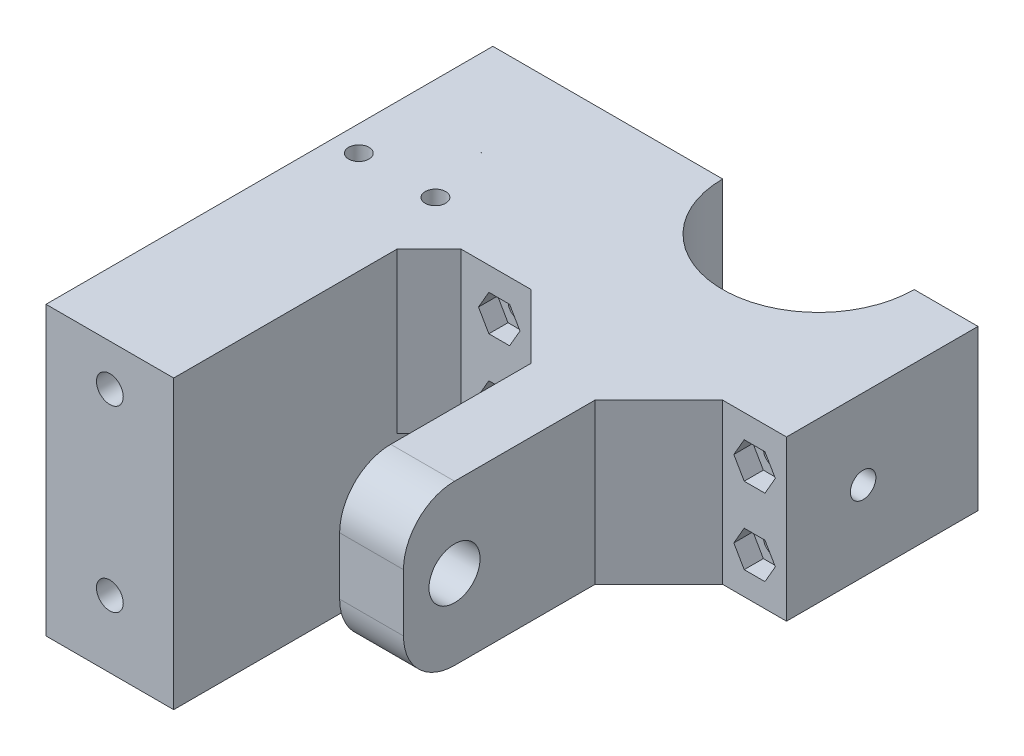
SolidWorks part; units mm, degrees
ref_plane "Спереди" through (0, 0, 0) normal (0, 0, 1) x (1, 0, 0)
ref_plane "Сверху" through (0, 0, 0) normal (0, 1, 0) x (1, 0, 0)
ref_plane "Справа" through (0, 0, 0) normal (1, 0, 0) x (0, 0, -1)
sketch "Sketch1" plane through (0, 0, 0) normal (0, 1, 0) x (1, 0, 0)
  line L0 (26.0276, -8) -> (-23.9724, -8) construction
  line L1 (-13.9724, -8) -> (-23.9724, -8)
  line L2 (-23.9724, -8) -> (-23.9724, -38)
  line L3 (-23.9724, -38) -> (-3.9724, -38)
  line L4 (-3.9724, -38) -> (-3.9724, -78)
  line L5 (-3.9724, -78) -> (6.0276, -78)
  line L6 (6.0276, -78) -> (6.0276, -38)
  line L7 (6.0276, -38) -> (26.0276, -38)
  line L8 (26.0276, -38) -> (26.0276, -8)
  line L9 (16.0276, -8) -> (26.0276, -8)
  circle A0 centre (1.0276, -8) radius 15 construction
  arc A1 (-13.9724, -8) -> (16.0276, -8) centre (1.0276, -8) ccw
  dimension "D2" = 30
  dimension "D1" = 30
  dimension "D3" = 10
  dimension "D4" = 40
  dimension "D5" = 50
extrude "Boss-Extrude1" add sketch "Sketch1" along normal blind 25
sketch "Sketch2" plane through (-3.9724, 0, 0) normal (-1, 0, 0) x (0, 0, 1)
  line L0 (78, 12.5) -> (38, 12.5) construction
  line L1 (78, 25) -> (78, 0) construction
  line L2 (38, 25) -> (38, 0) construction
  circle A0 centre (70, 12.5) radius 4
  dimension "D1" = 8
  dimension "D2" = 8
extrude "Cut-Extrude1" cut sketch "Sketch2" against normal through all
sketch "Sketch3" plane through (0, 0, 8) normal (0, 0, -1) x (-1, 0, 0)
  line L0 (-21.0276, 0) -> (-21.0276, 25) construction
  line L1 (-26.0276, 0) -> (-16.0276, 0) construction
  line L2 (-26.0276, 25) -> (-16.0276, 25) construction
  line L3 (18.9724, 0) -> (18.9724, 25) construction
  line L4 (13.9724, 0) -> (23.9724, 0) construction
  line L5 (13.9724, 25) -> (23.9724, 25) construction
  line L6 (-21.0276, 6.5) -> (18.9724, 6.5) construction
  line L7 (-21.0276, 18.5) -> (18.9724, 18.5) construction
  circle A0 centre (-21.0276, 6.5) radius 1.6
  circle A1 centre (-21.0276, 18.5) radius 1.6
  circle A2 centre (18.9724, 6.5) radius 1.6
  circle A3 centre (18.9724, 18.5) radius 1.6
  point P16 (-21.0276, 12.5)
  dimension "D2" = 3.2
  dimension "D3" = 12
  dimension "D4" = 6
extrude "Cut-Extrude2" cut sketch "Sketch3" against normal through all
sketch "Sketch4" plane through (0, 0, 38) normal (0, 0, 1) x (1, 0, 0)
  line L1 (24.2776, 18.5) -> (22.6526, 21.3146)
  line L2 (22.6526, 21.3146) -> (19.4026, 21.3146)
  line L3 (19.4026, 21.3146) -> (17.7776, 18.5)
  line L4 (17.7776, 18.5) -> (19.4026, 15.6854)
  line L5 (19.4026, 15.6854) -> (22.6526, 15.6854)
  line L6 (22.6526, 15.6854) -> (24.2776, 18.5)
  line L7 (24.2776, 6.5) -> (22.6526, 9.3146)
  line L8 (22.6526, 9.3146) -> (19.4026, 9.3146)
  line L9 (19.4026, 9.3146) -> (17.7776, 6.5)
  line L10 (17.7776, 6.5) -> (19.4026, 3.6854)
  line L11 (19.4026, 3.6854) -> (22.6526, 3.6854)
  line L12 (22.6526, 3.6854) -> (24.2776, 6.5)
  line L13 (-15.7224, 18.5) -> (-17.3474, 21.3146)
  line L14 (-17.3474, 21.3146) -> (-20.5974, 21.3146)
  line L15 (-20.5974, 21.3146) -> (-22.2224, 18.5)
  line L16 (-22.2224, 18.5) -> (-20.5974, 15.6854)
  line L17 (-20.5974, 15.6854) -> (-17.3474, 15.6854)
  line L18 (-17.3474, 15.6854) -> (-15.7224, 18.5)
  line L19 (-15.7224, 6.5) -> (-17.3474, 9.3146)
  line L20 (-17.3474, 9.3146) -> (-20.5974, 9.3146)
  line L21 (-20.5974, 9.3146) -> (-22.2224, 6.5)
  line L22 (-22.2224, 6.5) -> (-20.5974, 3.6854)
  line L23 (-20.5974, 3.6854) -> (-17.3474, 3.6854)
  line L24 (-17.3474, 3.6854) -> (-15.7224, 6.5)
  circle A0 centre (21.0276, 18.5) radius 3.25 construction
  circle A1 centre (21.0276, 6.5) radius 3.25 construction
  circle A2 centre (-18.9724, 18.5) radius 3.25 construction
  circle A3 centre (-18.9724, 6.5) radius 3.25 construction
  dimension "D1" = 6.5
extrude "Cut-Extrude3" cut sketch "Sketch4" against normal blind 3
fillet "Fillet2" radius 8 2 edges at (1.0276, 0, 78) (1.0276, 25, 78)
chamfer "Chamfer2" distance 10 angle 45 2 edges at (6.0276, 12.5, 38) (-3.9724, 12.5, 38)
sketch "Sketch5" plane through (-23.9724, 0, 0) normal (-1, 0, 0) x (0, 0, 1)
  line L0 (8, 12.5) -> (38, 12.5) construction
  line L1 (8, 25) -> (8, 0) construction
  line L2 (38, 25) -> (38, 0) construction
  line L4 (38, 25) -> (8, 25)
  line L5 (38, 25) -> (38, 0)
  line L6 (38, 0) -> (8, 0)
  line L7 (8, 25) -> (8, 0)
  line L8 (38, 25) -> (8, 0) construction
  line L9 (38, 0) -> (8, 25) construction
  point P6 (23, 12.5)
extrude "Boss-Extrude2" add sketch "Sketch5" along normal blind 26
sketch "Sketch6" plane through (0, 0, 38) normal (0, 0, 1) x (1, 0, 0)
  line L0 (-39.9701, 0) -> (-39.9701, 25) construction
  line L1 (-49.9724, 0) -> (-13.9724, 0) construction
  line L2 (-49.9724, 25) -> (-13.9724, 25) construction
  line L4 (-29.9679, 25) -> (-49.9724, 25)
  line L5 (-29.9679, 25) -> (-29.9679, 0)
  line L6 (-29.9679, 0) -> (-49.9724, 0)
  line L7 (-49.9724, 25) -> (-49.9724, 0)
  line L8 (-29.9679, 25) -> (-49.9724, 0) construction
  line L9 (-29.9679, 0) -> (-49.9724, 25) construction
  point P6 (-39.9701, 12.5)
  dimension "D1" = 20.0045
extrude "Boss-Extrude3" add sketch "Sketch6" along normal blind 40
sketch "Sketch7" plane through (0, 0, 0) normal (0, -1, 0) x (1, 0, 0)
  line L0 (-29.9679, 58) -> (-49.9724, 58) construction
  line L1 (-29.9679, 78) -> (-29.9679, 38) construction
  line L2 (-49.9724, 8) -> (-49.9724, 78) construction
  line L3 (-49.9724, 78) -> (-29.9679, 78) construction
  line L4 (-45.1701, 68.2) -> (-34.7701, 68.2)
  line L5 (-45.1701, 68.2) -> (-45.1701, 47.8)
  line L6 (-45.1701, 47.8) -> (-34.7701, 47.8)
  line L7 (-34.7701, 68.2) -> (-34.7701, 47.8)
  line L8 (-45.1701, 68.2) -> (-34.7701, 47.8) construction
  line L9 (-45.1701, 47.8) -> (-34.7701, 68.2) construction
  point P6 (-39.9701, 58)
  dimension "D1" = 10.4
  dimension "D2" = 20.4
  dimension "D3" = 20
extrude "Cut-Extrude4" cut sketch "Sketch7" against normal blind 23
sketch "Sketch9" plane through (0, 0, 0) normal (0, -1, 0) x (1, 0, 0)
  line L0 (-45.1701, 58) -> (-34.7701, 58) construction
  line L1 (-45.1701, 68.2) -> (-45.1701, 47.8) construction
  line L2 (-34.7701, 47.8) -> (-34.7701, 68.2) construction
  line L4 (-49.9724, 78) -> (-29.9679, 78)
  line L5 (-49.9724, 78) -> (-49.9724, 38)
  line L6 (-49.9724, 38) -> (-29.9679, 38)
  line L7 (-29.9679, 78) -> (-29.9679, 38)
  line L8 (-49.9724, 78) -> (-29.9679, 38) construction
  line L9 (-49.9724, 38) -> (-29.9679, 78) construction
  line L10 (-45.1701, 68.2) -> (-34.7701, 68.2)
  line L11 (-45.1701, 68.2) -> (-45.1701, 47.8)
  line L12 (-45.1701, 47.8) -> (-34.7701, 47.8)
  line L13 (-34.7701, 68.2) -> (-34.7701, 47.8)
  line L14 (-45.1701, 68.2) -> (-34.7701, 47.8) construction
  line L15 (-45.1701, 47.8) -> (-34.7701, 68.2) construction
  point P6 (-39.9701, 58)
  point P12 (-39.9701, 58)
extrude "Boss-Extrude4" add sketch "Sketch9" along normal blind 20
sketch "Sketch10" plane through (0, 0, 78) normal (0, 0, 1) x (1, 0, 0)
  line L0 (-39.9701, -20) -> (-39.9701, 25) construction
  line L1 (-29.9679, -20) -> (-49.9724, -20) construction
  line L2 (-29.9679, 25) -> (-49.9724, 25) construction
  circle A0 centre (-39.9701, -9.5) radius 2.1
  circle A1 centre (-39.9701, 18.5) radius 2.1
  point P16 (-39.9701, 2.5)
  dimension "D1" = 28
  dimension "D2" = 4.2
  dimension "D3" = 12
extrude "Cut-Extrude6" cut sketch "Sketch10" against normal through all
chamfer "Chamfer5" distance 5 angle 45 1 edges at (-29.9679, 12.5, 38)
sketch "Sketch11" plane through (26.0276, 0, 0) normal (1, 0, 0) x (0, 0, -1)
  line L0 (-8, 12.5) -> (-38, 12.5) construction
  line L1 (-8, 25) -> (-8, 0) construction
  line L2 (-38, 25) -> (-38, 0) construction
  circle A0 centre (-26, 12.5) radius 2
  dimension "D1" = 4
  dimension "D2" = 18
extrude "Cut-Extrude7" cut sketch "Sketch11" against normal through all
sketch "Sketch12" plane through (0, 0, 38) normal (0, 0, -1) x (-1, 0, 0)
  line L0 (29.9679, -10) -> (49.9724, -10) construction
  line L1 (29.9679, -20) -> (29.9679, 0) construction
  line L2 (49.9724, -20) -> (49.9724, 0) construction
  line L4 (49.9724, -20) -> (29.9679, -20)
  line L5 (49.9724, -20) -> (49.9724, 0)
  line L6 (49.9724, 0) -> (29.9679, 0)
  line L7 (29.9679, -20) -> (29.9679, 0)
  line L8 (49.9724, -20) -> (29.9679, 0) construction
  line L9 (49.9724, 0) -> (29.9679, -20) construction
  circle A0 centre (39.9701, -9.5) radius 2.1
  point P6 (39.9701, -10)
extrude "Boss-Extrude5" add sketch "Sketch12" along normal up to surface (30 mm away) up to face at (-37.8701, 18.5, 8)
sketch "Sketch13" plane through (0, -20, 0) normal (0, -1, 0) x (1, 0, 0)
  line L0 (-29.9679, 33) -> (-49.9724, 33) construction
  line L1 (-29.9679, 8) -> (-29.9679, 78) construction
  line L2 (-49.9724, 78) -> (-49.9724, 8) construction
  line L3 (-49.9724, 8) -> (-29.9679, 8) construction
  circle A0 centre (-33.9701, 33) radius 1.6
  circle A1 centre (-45.9701, 33) radius 1.6
  point P10 (-39.9701, 33)
  dimension "D1" = 3.2
  dimension "D2" = 12
  dimension "D3" = 6
  dimension "D4" = 25
extrude "Cut-Extrude8" cut sketch "Sketch13" against normal through all
